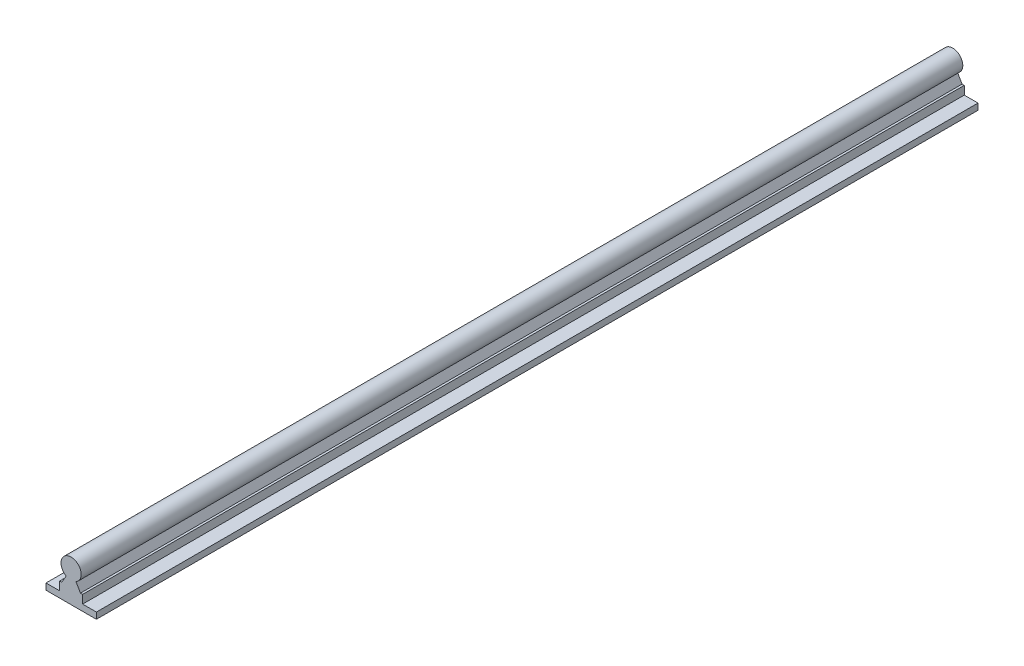
SolidWorks part; units mm, degrees
ref_plane "Plan de face" through (0, 0, 0) normal (0, 0, 1) x (1, 0, 0)
ref_plane "Plan de dessus" through (0, 0, 0) normal (0, 1, 0) x (1, 0, 0)
ref_plane "Plan de droite" through (0, 0, 0) normal (1, 0, 0) x (0, 0, -1)
sketch "Esquisse1" plane through (0, 0, 0) normal (0, 0, 1) x (1, 0, 0)
  line L0 (-25.9313, -2.761) -> (-15.1813, -2.761)
  line L1 (-15.1813, -2.761) -> (-15.1813, 3.939)
  line L2 (-15.1813, 3.939) -> (-13.4531, 3.939)
  line L3 (-13.4531, 3.939) -> (-9.9313, 10.039)
  line L5 (-2.0896, 10.039) -> (1.4322, 3.939)
  line L6 (1.4322, 3.939) -> (3.1604, 3.939)
  line L7 (3.1604, 3.939) -> (3.1604, -2.761)
  line L8 (3.1604, -2.761) -> (14.0687, -2.761)
  line L9 (14.0687, -2.761) -> (14.0687, -7.761)
  line L14 (14.0687, -7.761) -> (-25.9313, -7.761)
  line L15 (-25.9313, -7.761) -> (-25.9313, -2.761)
  line L16 (-25.9313, -2.761) -> (-25.9155, -2.8404)
  arc A1 (-9.9313, 10.039) -> (-2.0896, 10.039) centre (-6.0104, 17.0123) cw
  dimension "D1" = 8
extrude "Boss.-Extru.1" add sketch "Esquisse1" along normal blind 700 contours L0 L1 L2 L3 A1 L5 L6 L7 L8 L9 L14 L15
